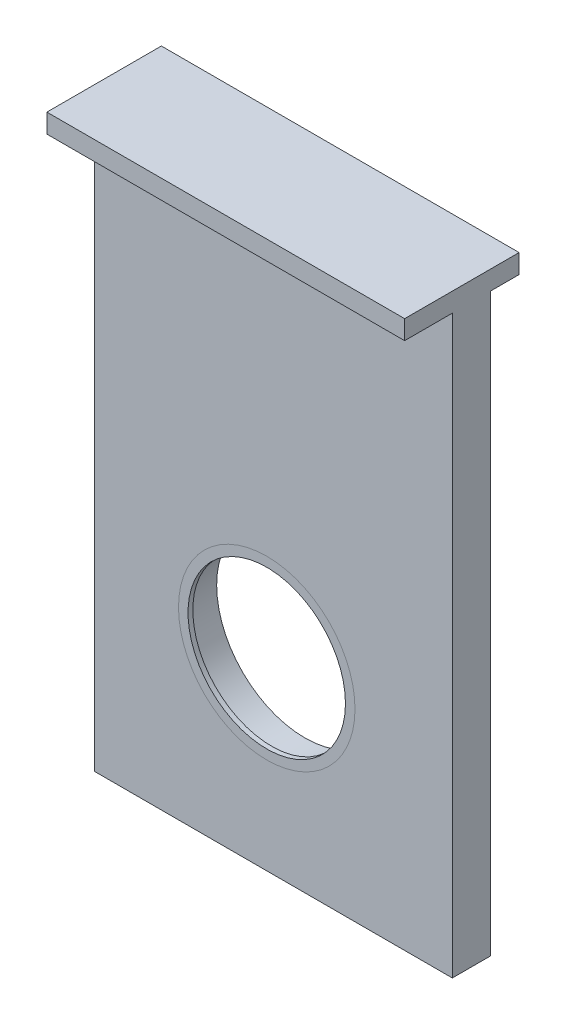
SolidWorks part; units mm, degrees
ref_plane "Front Plane" through (0, 0, 0) normal (0, 0, 1) x (1, 0, 0)
ref_plane "Top Plane" through (0, 0, 0) normal (0, 1, 0) x (1, 0, 0)
ref_plane "Right Plane" through (0, 0, 0) normal (1, 0, 0) x (0, 0, -1)
sketch "Sketch12" plane through (0, 0, 0) normal (0, 0, 1) x (1, 0, 0)
  line L0 (62.1258, 0) -> (62.1258, 124.71)
  line L1 (62.1258, 124.71) -> (137.1258, 124.71)
  line L2 (62.1258, 0) -> (137.1258, 0)
  line L3 (137.1258, 124.71) -> (137.1258, 0)
  circle A0 centre (99.6258, 37.5) radius 25.4
  circle A1 centre (99.6258, 37.5) radius 6.5
  dimension "D3" = 50.8
  dimension "D4" = 13
  dimension "D1" = 124.71
  dimension "D2" = 75
extrude "Boss-Extrude10" add sketch "Sketch12" along normal blind 8 separate body contours L1 L3 L2 L0
sketch "Sketch15" plane through (0, 0, 8) normal (0, 0, 1) x (1, 0, 0)
  circle A0 centre (98.2196, 38.6276) radius 25.4
  dimension "D1" = 50.8
sketch "Sketch24" plane through (0, 0, 8) normal (0, 0, 1) x (1, 0, 0)
  line L0 (62.1258, 124.71) -> (62.1258, 120.71)
  line L1 (62.1258, 0) -> (62.1258, 124.71) construction
  line L2 (62.1258, 120.71) -> (137.1258, 120.71)
  line L3 (137.1258, 124.71) -> (137.1258, 0) construction
  line L4 (137.1258, 120.71) -> (137.1258, 124.71)
  line L5 (137.1258, 124.71) -> (62.1258, 124.71)
  dimension "D1" = 4
extrude "Boss-Extrude13" add sketch "Sketch24" along normal blind 10 and the other way blind 14
sketch "Sketch25" plane through (0, 0, 8) normal (0, 0, 1) x (1, 0, 0)
  circle A0 centre (98.2196, 38.6276) radius 18.5
  dimension "D1" = 37
extrude "Cut-Extrude1" cut sketch "Sketch25" against normal through all
sketch "Sketch26" plane through (0, 0, 8) normal (0, 0, 1) x (1, 0, 0)
  circle A0 centre (98.2196, 38.6276) radius 16.5
  circle A1 centre (98.2196, 38.6276) radius 18.5
  dimension "D1" = 37
  dimension "D2" = 2
extrude "Boss-Extrude15" add sketch "Sketch26" against normal blind 1 separate body
sketch "Sketch27" plane through (0, 0, 0) normal (0, 0, -1) x (-1, 0, 0)
  line L0 (-98.2196, 38.6276) -> (-98.2196, 124.71)
  line L1 (-137.1258, 124.71) -> (-62.1258, 124.71) construction
